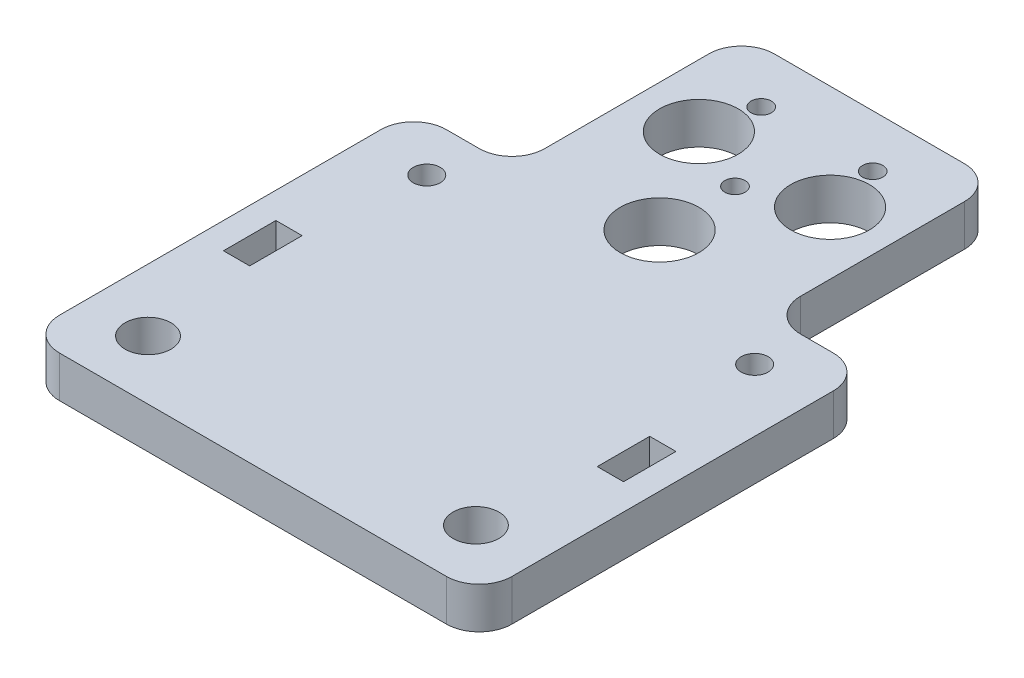
SolidWorks part; units mm, degrees
ref_plane "Front Plane" through (0, 0, 0) normal (0, 0, 1) x (1, 0, 0)
ref_plane "Top Plane" through (0, 0, 0) normal (0, 1, 0) x (1, 0, 0)
ref_plane "Right Plane" through (0, 0, 0) normal (1, 0, 0) x (0, 0, -1)
sketch "Sketch1" plane through (0, 0, 0) normal (0, 1, 0) x (1, 0, 0)
  line L0 (15, 94) -> (15, 59)
  line L1 (0, 0) -> (69, 0)
  line L2 (0, 0) -> (0, 59)
  line L3 (15, 94) -> (54, 94)
  line L4 (69, 0) -> (69, 59)
  line L5 (15, 59) -> (0, 59)
  line L6 (54, 94) -> (54, 59)
  line L7 (54, 59) -> (69, 59)
  line L8 (24.5, 78) -> (44.5, 78) construction
  line L9 (4, 34) -> (8, 34)
  line L10 (4, 34) -> (4, 26)
  line L11 (4, 26) -> (8, 26)
  line L12 (8, 34) -> (8, 26)
  line L13 (65, 34) -> (61, 34)
  line L14 (65, 34) -> (65, 26)
  line L15 (65, 26) -> (61, 26)
  line L16 (61, 34) -> (61, 26)
  line L17 (9.5, 51.5) -> (59.5, 51.5) construction
  line L18 (9.5, 51.5) -> (9.5, 9) construction
  line L19 (9.5, 9) -> (59.5, 9) construction
  line L20 (59.5, 51.5) -> (59.5, 9) construction
  line L21 (34.5, 62) -> (34.5, 78) construction
  line L22 (43, 86) -> (26, 86) construction
  line L23 (34.5, 73.5) -> (34.5, 86) construction
  circle A0 centre (9.5, 51.5) radius 2.05
  circle A1 centre (59.5, 51.5) radius 2.05
  circle A2 centre (9.5, 9) radius 3.5
  circle A3 centre (59.5, 9) radius 3.5
  circle A4 centre (24.5, 78) radius 6
  circle A5 centre (44.5, 78) radius 6
  circle A6 centre (34.5, 62) radius 6
  circle A7 centre (34.5, 73.5) radius 1.55
  circle A8 centre (26, 86) radius 1.55
  circle A9 centre (43, 86) radius 1.55
  point P17 (6, 26)
  point P26 (34.5, 9)
  point P27 (34.5, 0)
  point P34 (34.5, 94)
  point P42 (34.5, 86)
  dimension "D15" = 7
  dimension "D16" = 7
  dimension "D17" = 4.1
  dimension "D18" = 4.1
  dimension "D25" = 12
  dimension "D26" = 12
  dimension "D27" = 12
  dimension "D31" = 3.1
  dimension "D32" = 3.1
  dimension "D33" = 3.1
  dimension "D1" = 94
  dimension "D2" = 69
  dimension "D3" = 15
  dimension "D4" = 15
  dimension "D5" = 35
  dimension "D6" = 35
  dimension "D7" = 8
  dimension "D8" = 8
  dimension "D9" = 4
  dimension "D10" = 4
  dimension "D11" = 4
  dimension "D12" = 4
  dimension "D13" = 26
  dimension "D14" = 26
  dimension "D19" = 9
  dimension "D20" = 42.5
  dimension "D21" = 50
  dimension "D22" = 78
  dimension "D23" = 20
  dimension "D24" = 16
  dimension "D28" = 12.5
  dimension "D29" = 8
  dimension "D30" = 17
extrude "Boss-Extrude1" add sketch "Sketch1" along normal blind 6.3
fillet "Fillet1" radius 5 8 edges at (54, 3.15, -59) (69, 3.15, 0) (69, 3.15, -59) (54, 3.15, -94) (15, 3.15, -59) (15, 3.15, -94) (0, 3.15, -59) (0, 3.15, 0)
